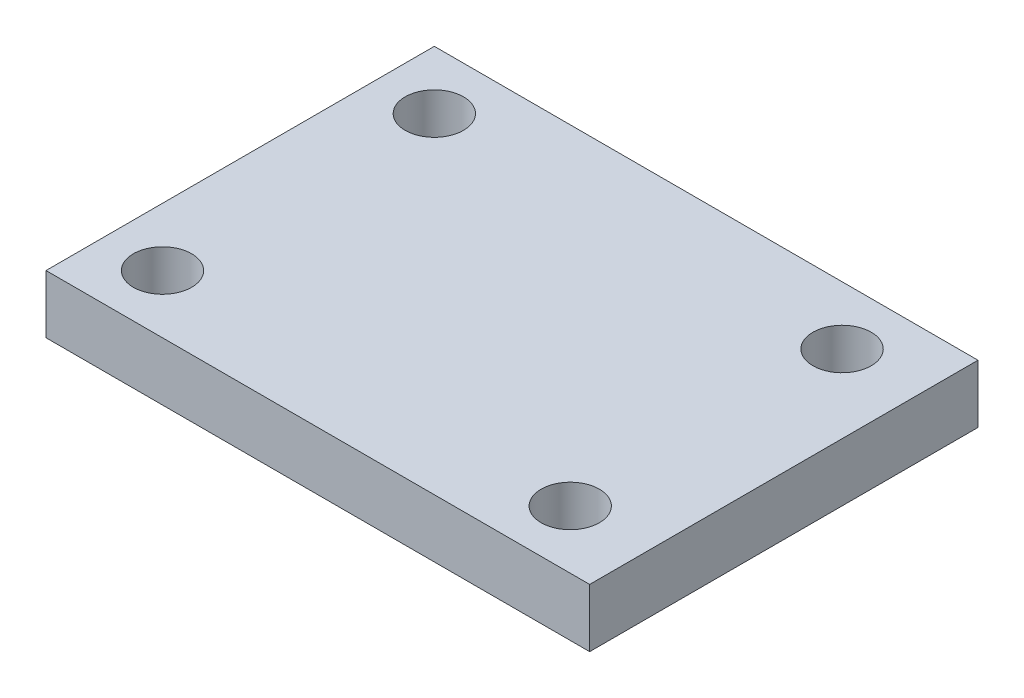
SolidWorks part; units mm, degrees
ref_plane "Front Plane" through (0, 0, 0) normal (0, 0, 1) x (1, 0, 0)
ref_plane "Top Plane" through (0, 0, 0) normal (0, 1, 0) x (1, 0, 0)
ref_plane "Right Plane" through (0, 0, 0) normal (1, 0, 0) x (0, 0, -1)
sketch "Sketch1" plane through (0, 0, 0) normal (0, 1, 0) x (1, 0, 0)
  line L1 (14, -10) -> (-14, -10)
  line L2 (14, -10) -> (14, 10)
  line L3 (14, 10) -> (-14, 10)
  line L4 (-14, -10) -> (-14, 10)
  line L5 (14, -10) -> (-14, 10) construction
  line L6 (14, 10) -> (-14, -10) construction
  point P0 (0, 0)
  dimension "D1" = 28
  dimension "D2" = 20
extrude "Boss-Extrude1" add sketch "Sketch1" along normal blind 3
hole_wizard "Ø3.0 (3) Diameter Hole1" positions "Sketch2" profile "Sketch3" hole size "Ø3.0" standard "ANSI Metric" end condition through all
sketch "Sketch2" plane through (0, 3, 0) normal (0, 1, 0) x (1, 0, 0)
  line L0 (14, 10) -> (-14, 10) construction
  line L1 (-14, 10) -> (-14, -10) construction
  point P0 (-11, 7)
  point P2 (-11, -7)
  point P4 (10, -7)
  point P6 (10, 7)
  dimension "D1" = 14
  dimension "D2" = 3
  dimension "D3" = 21
  dimension "D4" = 3
sketch "Sketch3" plane through (-11, 3, -7) normal (1, 0, 0) x (0, 0, 1)
  line L0 (0, 0) -> (0, 3)
  line L1 (0, 3) -> (1.5, 3)
  line L2 (1.5, 3) -> (1.5, 0)
  line L5 (1.5, 0) -> (0, 0)
  line L11 (0, -6.35) -> (0, 107.95) construction
  dimension "Thru Hole Dia." = 3
  dimension "Thru Hole Depth" = 3
